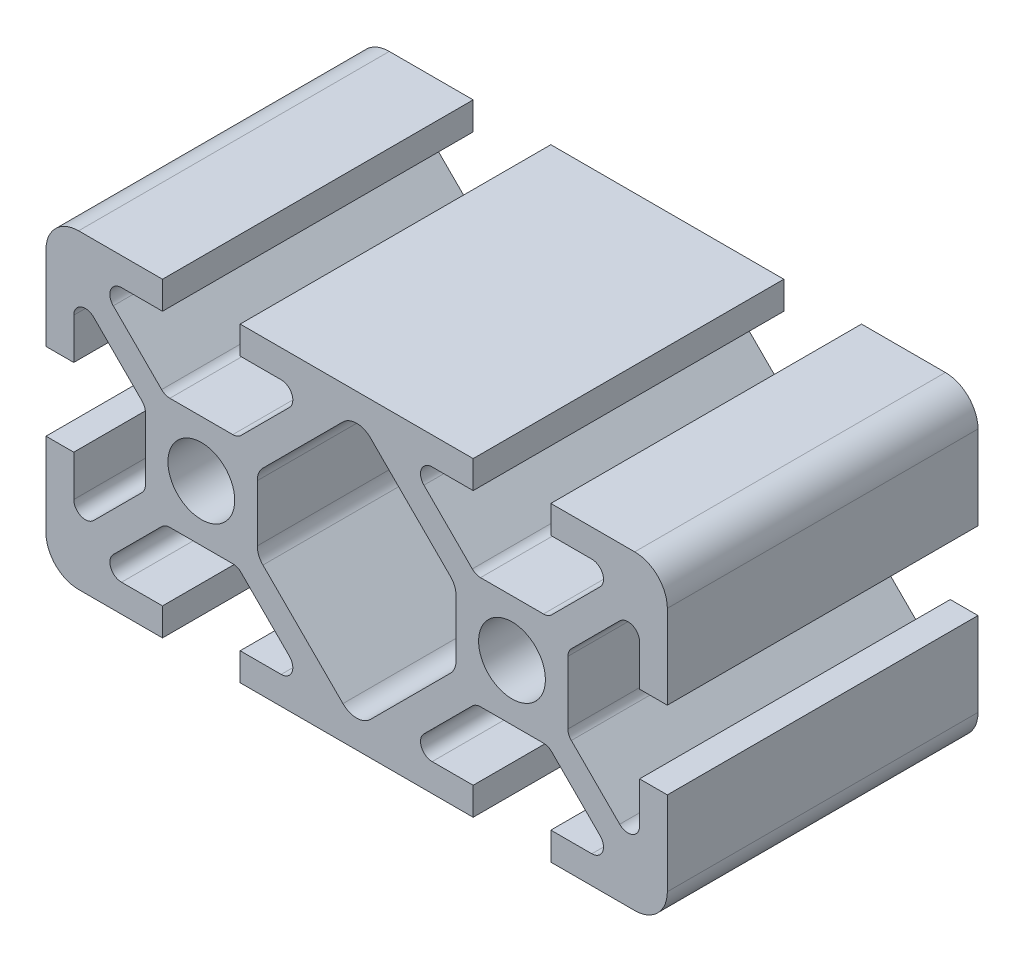
SolidWorks part; units mm, degrees
ref_plane "Front Plane" through (0, 0, 0) normal (0, 0, 1) x (1, 0, 0)
ref_plane "Top Plane" through (0, 0, 0) normal (0, 1, 0) x (1, 0, 0)
ref_plane "Right Plane" through (0, 0, 0) normal (1, 0, 0) x (0, 0, -1)
sketch "Sketch1" plane through (0, 0, 0) normal (0, 0, 1) x (1, 0, 0)
  line L0 (10, 10) -> (10, -10) construction
  line L1 (-20, 0) -> (20, 0) construction
  line L2 (12.5, -10) -> (20, -10)
  line L3 (20, -10) -> (20, -2.5)
  line L4 (12.5, -10) -> (12.5, -8.2134)
  line L5 (12.5, -8.2134) -> (16.95, -8.2134)
  line L6 (16.95, -8.2134) -> (12.3366, -3.6)
  line L7 (10, 0) -> (20, -10) construction
  line L8 (20, -2.5) -> (18.2134, -2.5)
  line L9 (18.2134, -2.5) -> (18.2134, -6.95)
  line L10 (18.2134, -6.95) -> (13.6, -2.3366)
  line L11 (15.9067, -4.6433) -> (14.6433, -5.9067) construction
  line L12 (0, 10) -> (0, -10) construction
  line L13 (0, -10) -> (-20, -10) construction
  line L14 (-10, 10) -> (10, 10) construction
  line L15 (20, 2.5) -> (20, -2.5) construction
  circle A0 centre (10, 0) radius 2.15
  arc A1 (15.5015, -8.2134) -> (15.9257, -7.1891) centre (15.5015, -7.6134) ccw construction
  point P8 (10, -3.6)
  point P16 (15.275, -5.275)
  point P30 (20, 0)
  dimension "Center Hole Diameter" = 4.3
  dimension "D3" = 0.6
  dimension "Rail Width" = 20
  dimension "T-Slot Width" = 5
  dimension "Slot Depth" = 6.4
  dimension "Rail Height" = 40
  dimension "Inner Slot Width" = 13.9
  dimension "Hole Spacing" = 20
sketch "Sketch2" plane through (0, 0, 0) normal (1, 0, 0) x (0, 0, -1)
  line L0 (-1524, -10) -> (1524, -10) construction
  line L1 (-1484, 0) -> (1484, 0) construction
  point P6 (-1484, 0)
  point P8 (1484, 0)
  dimension "Length" = 3048
  dimension "D1" = 40
sketch "Sketch3" plane through (0, 0, 0) normal (0, 0, 1) x (1, 0, 0)
  line L0 (12.5, -10) -> (17.9, -10)
  line L1 (12.5, -10) -> (20, -10) construction
  line L2 (12.5, -10) -> (12.5, -8.2134) construction
  line L3 (12.5, -8.2134) -> (16.95, -8.2134) construction
  line L4 (12.5, -8.2134) -> (12.5, -10)
  line L5 (12.5, -8.2134) -> (16.95, -8.2134)
  line L6 (10, -3.6) -> (12.3366, -3.6)
  line L7 (16.95, -8.2134) -> (12.3366, -3.6) construction
  line L8 (12.3366, -3.6) -> (16.95, -8.2134)
  line L9 (20, -10) -> (20, -2.5) construction
  line L10 (18.2134, -6.95) -> (13.6, -2.3366) construction
  line L11 (18.2134, -2.5) -> (18.2134, -6.95) construction
  line L12 (18.2134, -6.95) -> (18.2134, -2.5)
  line L13 (20, -2.5) -> (18.2134, -2.5) construction
  line L14 (18.2134, -2.5) -> (20, -2.5)
  line L15 (20, -2.5) -> (20, -7.9)
  line L16 (18.2134, -6.95) -> (13.6, -2.3366)
  line L17 (13.6, 0) -> (13.6, -2.3366)
  line L18 (-20, 0) -> (20, 0) construction
  line L19 (10, -3.6) -> (10, -2.15)
  line L20 (10, 10) -> (10, -10) construction
  line L21 (13.6, 0) -> (12.15, 0)
  arc A5 (17.9, -10) -> (20, -7.9) centre (17.9, -7.9) ccw
  circle A10 centre (10, 0) radius 2.15 construction
  arc A11 (10, -2.15) -> (12.15, 0) centre (10, 0) ccw
  dimension "D1" = 2.1
extrude "Boss-Extrude1" add sketch "Sketch3" along normal mid plane 3048
sketch "Sketch4" plane through (0, 0, 0) normal (0, 0, 1) x (1, 0, 0)
  line L0 (10, -3.6) -> (7.6634, -3.6)
  line L4 (7.6634, -3.6) -> (3.05, -8.2134)
  line L5 (3.05, -8.2134) -> (7.5, -8.2134)
  line L6 (7.5, -8.2134) -> (7.5, -10)
  line L18 (7.5, -10) -> (0, -10)
  line L19 (12.5, -10) -> (12.5, -8.2134) construction
  line L20 (12.5, -8.2134) -> (16.95, -8.2134) construction
  line L21 (10, -3.6) -> (12.3366, -3.6) construction
  line L22 (16.95, -8.2134) -> (12.3366, -3.6) construction
  line L23 (0, -8.7366) -> (6.4, -2.3366)
  line L24 (0, 10) -> (0, -10) construction
  line L25 (6.4, -2.3366) -> (6.4, 0)
  line L26 (-20, 0) -> (20, 0) construction
  line L27 (6.4, 0) -> (7.85, 0)
  line L28 (13.6, 0) -> (12.15, 0) construction
  line L29 (0, -8.7366) -> (0, -10)
  line L30 (10, -2.15) -> (10, -3.6)
  circle A4 centre (10, 0) radius 2.15 construction
  arc A5 (7.85, 0) -> (10, -2.15) centre (10, 0) ccw
extrude "Boss-Extrude2" add sketch "Sketch4" along normal mid plane 3048
mirror "Mirror1" about plane through (0, 0, 0) normal (1, 0, 0) of bodies 137 134
mirror "Mirror2" about plane through (0, 0, 0) normal (0, 1, 0) of bodies 135
fillet "Fillet1" radius 0.75 24 edges at (-3.05, -8.2134, 0) (-7.6634, -3.6, 0) (-12.3366, -3.6, 0) (-16.95, -8.2134, 0) (12.3366, -3.6, 0) (7.6634, -3.6, 0) (-18.2134, -6.95, 0) (-13.6, -2.3366, 0) (-18.2134, 6.95, 0) (-16.95, 8.2134, 0) (-12.3366, 3.6, 0) (-7.6634, 3.6, 0) (-13.6, 2.3366, 0) (-3.05, 8.2134, 0) (3.05, 8.2134, 0) (13.6, -2.3366, 0) (18.2134, 6.95, 0) (13.6, 2.3366, 0) (7.6634, 3.6, 0) (12.3366, 3.6, 0) (16.95, 8.2134, 0) (18.2134, -6.95, 0) (16.95, -8.2134, 0) (3.05, -8.2134, 0)
fillet "Fillet2" radius 1.25 6 edges at (0, -8.7366, 0) (-6.4, -2.3366, 0) (0, 8.7366, 0) (-6.4, 2.3366, 0) (6.4, -2.3366, 0) (6.4, 2.3366, 0)
sketch "Sketch5" plane through (20, 0, 0) normal (1, 0, 0) x (0, 0, -1)
  line L0 (-1524, -10) -> (1524, -10) construction
  line L1 (1524, 10) -> (-1504, 10)
  line L2 (1524, 10) -> (1524, -10)
  line L3 (1524, -10) -> (-1504, -10)
  line L4 (-1504, 10) -> (-1504, -10)
  line L5 (-1524, 7.9) -> (-1524, 2.5) construction
  dimension "D1" = 20
extrude "Cut-Extrude1" cut sketch "Sketch5" against normal through all
equation "\"D1@Sketch3\" = \"D3@Sketch1\" * 3.5"
equation "\"D1@Boss-Extrude1\" = \"Length@Sketch2\""
equation "\"D1@Boss-Extrude2\" = \"Length@Sketch2\""
equation "\"D1@Sketch2\"=\"Rail Height@Sketch1\""
